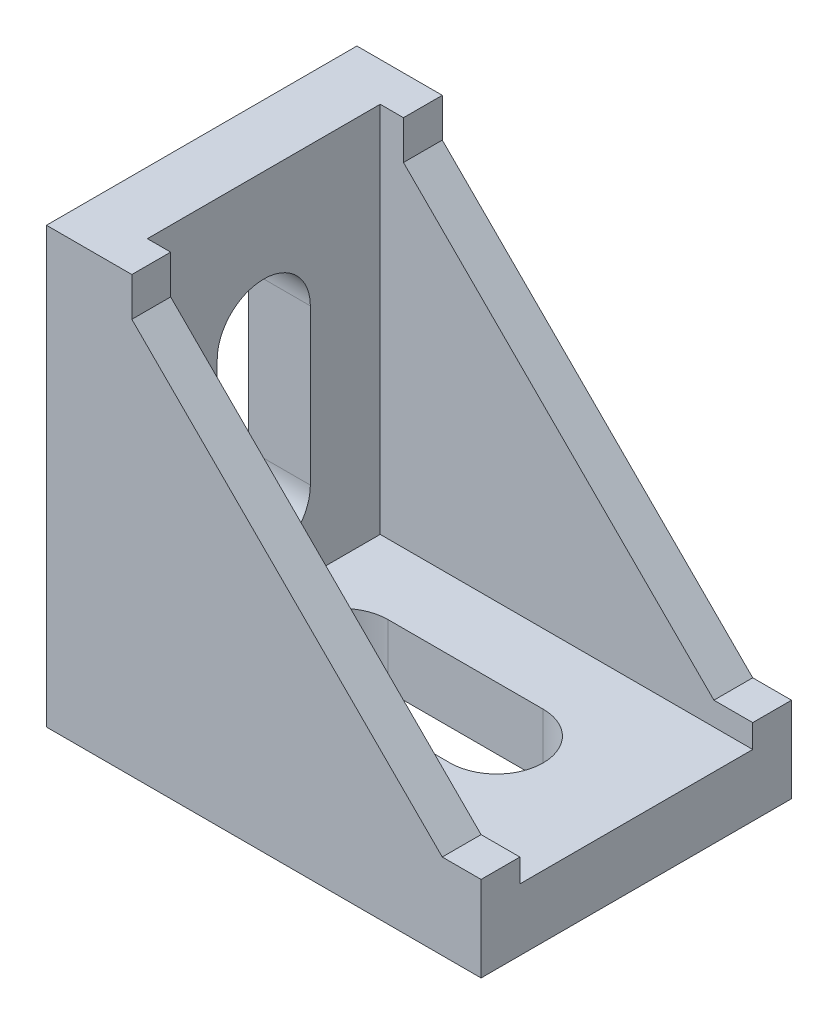
SolidWorks part; units mm, degrees
ref_plane "Front Plane" through (0, 0, 0) normal (0, 0, 1) x (1, 0, 0)
ref_plane "Top Plane" through (0, 0, 0) normal (0, 1, 0) x (1, 0, 0)
ref_plane "Right Plane" through (0, 0, 0) normal (1, 0, 0) x (0, 0, -1)
sketch "Sketch1" plane through (0, 0, 0) normal (0, 0, 1) x (1, 0, 0)
  line L1 (0, 0) -> (28, 0)
  line L2 (0, 0) -> (0, 28)
  line L3 (0, 28) -> (28, 28)
  line L4 (28, 0) -> (28, 28)
extrude "Boss-Extrude1" add sketch "Sketch1" along normal blind 20
sketch "Sketch2" plane through (0, 0, 20) normal (0, 0, 1) x (1, 0, 0)
  line L2 (5.5, 28) -> (5.5, 0)
  line L3 (5.5, 29.4261) -> (5.5, 25.5)
  line L5 (5.5, 29.4261) -> (30.2443, 29.4261)
  line L6 (30.2443, 29.4261) -> (30.2443, 5.5)
  line L10 (5.5, 25.5) -> (25.5, 5.5)
  line L14 (25.5, 5.5) -> (30.2443, 5.5)
  dimension "D1" = 5.5
extrude "Cut-Extrude1" cut sketch "Sketch2" against normal through all
ref_plane "Plane1" through (4, 0, 0) normal (-1, 0, 0) x (0, 0, 1)
sketch "Sketch3" plane through (4, 0, 0) normal (-1, 0, 0) x (0, 0, 1)
  line L2 (20, 4) -> (0, 4)
  line L3 (17.5, 4) -> (2.5, 4)
  line L5 (2.5, 25.5) -> (2.5, 5.5)
  line L6 (2.5, 30.8809) -> (2.5, 4)
  line L7 (17.5, 30.8809) -> (2.5, 30.8809)
  line L8 (17.5, 25.5) -> (17.5, 5.5)
  line L9 (17.5, 30.8809) -> (17.5, 4)
  dimension "D1" = 4
  dimension "D2" = 2.5
  dimension "D3" = 2.5
extrude "Cut-Extrude2" cut sketch "Sketch3" against normal up to surface (24 mm away) up to face at (28, 2.75, 10)
sketch "Sketch4" plane through (4, 0, 0) normal (1, 0, 0) x (0, 0, -1)
  line L4 (-13, 19) -> (-13, 9)
  line L7 (-7, 19) -> (-7, 9)
  arc A0 (-7, 19) -> (-13, 19) centre (-10, 19) ccw
  arc A1 (-13, 9) -> (-7, 9) centre (-10, 9) ccw
extrude "Cut-Extrude3" cut sketch "Sketch4" against normal up to surface (4 mm away) up to face at (0, 14, 10)
sketch "Sketch5" plane through (0, 4, 0) normal (0, 1, 0) x (1, 0, 0)
  line L4 (19, -13) -> (9, -13)
  line L7 (9, -7) -> (19, -7)
  arc A0 (19, -13) -> (19, -7) centre (19, -10) ccw
  arc A1 (9, -7) -> (9, -13) centre (9, -10) ccw
extrude "Cut-Extrude4" cut sketch "Sketch5" against normal up to surface (4 mm away) up to face at (14, 0, 10)
sketch "Sketch6" plane through (0, 0, 0) normal (-1, 0, 0) x (0, 0, 1)
  line L1 (12.9, 26) -> (7.1, 26)
  line L3 (12.9, 27) -> (7.1, 27)
  line L5 (7.1, 27) -> (7.1, 26)
  line L6 (12.9, 27) -> (12.9, 26)
  line L8 (20, 27) -> (0, 27) construction
  line L9 (20, 26) -> (0, 26) construction
  dimension "D2" = 1
extrude "Boss-Extrude2" add sketch "Sketch6" along normal blind 1
sketch "Sketch7" plane through (0, 0, 0) normal (0, -1, 0) x (1, 0, 0)
  line L1 (26, 12.9) -> (26, 7.1)
  line L3 (27, 12.9) -> (27, 7.1)
  line L4 (27, 20) -> (27, 0) construction
  line L5 (27, 12.9) -> (26, 12.9)
  line L6 (27, 7.1) -> (26, 7.1)
  line L7 (26, 20) -> (26, 0) construction
extrude "Boss-Extrude3" add sketch "Sketch7" along normal blind 1
